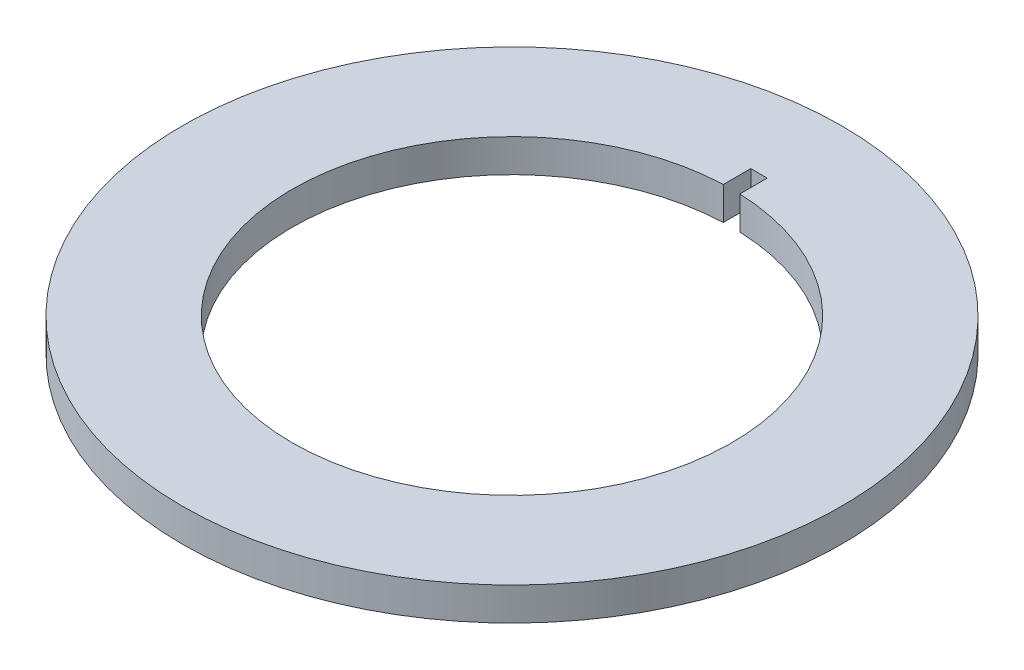
SolidWorks part; units mm, degrees
ref_plane "Plan de face" through (0, 0, 0) normal (0, 0, 1) x (1, 0, 0)
ref_plane "Plan de dessus" through (0, 0, 0) normal (0, 1, 0) x (1, 0, 0)
ref_plane "Plan de droite" through (0, 0, 0) normal (1, 0, 0) x (0, 0, -1)
sketch "Esquisse1" plane through (0, 0, 0) normal (0, 1, 0) x (1, 0, 0)
  line L0 (0, -1000) -> (0, 49000) construction
  line L1 (-0.75, -1000) -> (-0.75, 49000) construction
  line L2 (0.75, -1000) -> (0.75, 49000) construction
  line L3 (0.75, 22.4875) -> (-0.75, 22.4875)
  line L4 (-0.75, 22.4875) -> (-0.75, 19.9859)
  line L5 (0.75, 22.4875) -> (0.75, 19.9859)
  arc A0 (-0.75, 19.9859) -> (0.75, 19.9859) centre (0, 0) ccw
  circle A1 centre (0, 0) radius 30
  circle A2 centre (0, 0) radius 22.5 construction
  circle A4 centre (0, 0) radius 20 construction
  point P15 (18.887, 5.7743)
  dimension "D2" = 40
  dimension "D1" = 10
  dimension "D3" = 2.5
  dimension "D4" = 0.75
  dimension "D5" = 0.75
extrude "Boss.-Extru.1" add sketch "Esquisse1" along normal blind 3
